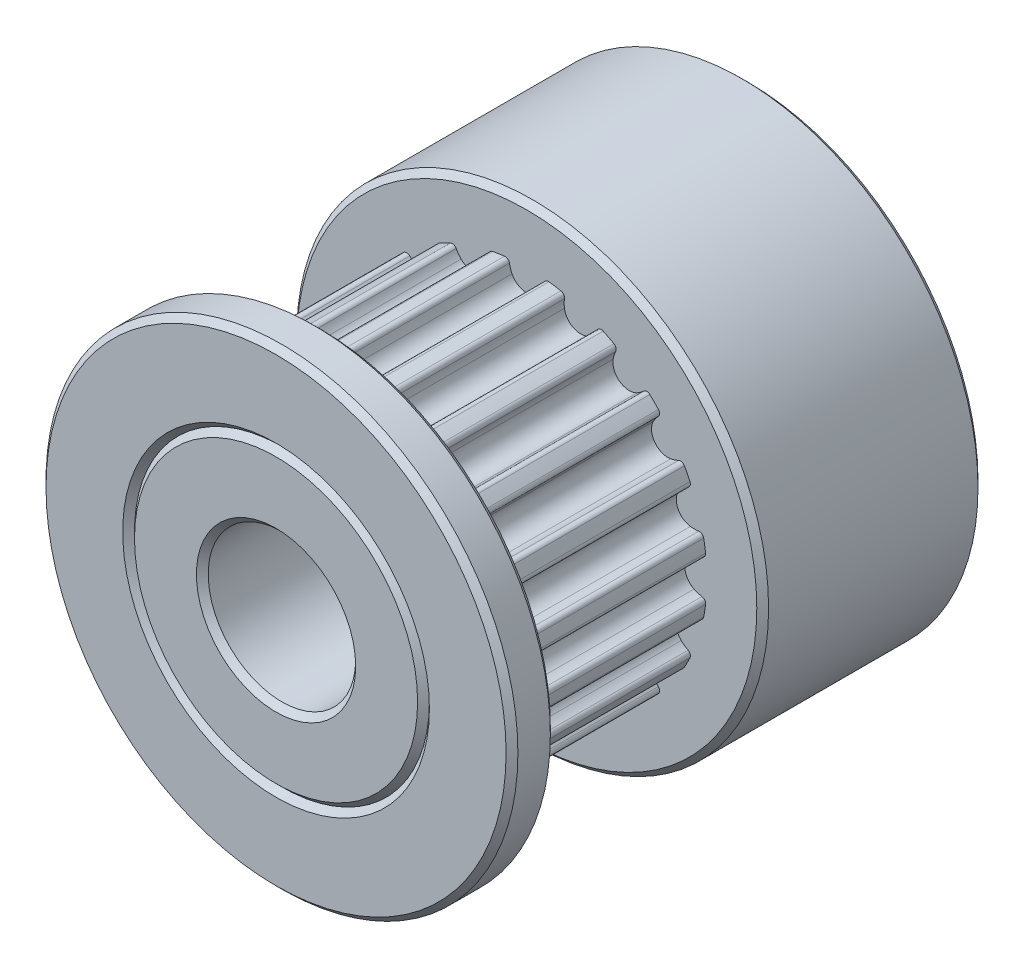
SolidWorks part; units mm, degrees
material "2219-O"
ref_plane "Спереди" through (0, 0, 0) normal (0, 0, 1) x (1, 0, 0)
ref_plane "Сверху" through (0, 0, 0) normal (0, 1, 0) x (1, 0, 0)
ref_plane "Справа" through (0, 0, 0) normal (1, 0, 0) x (0, 0, -1)
sketch "Эскиз2" plane through (0, 0, 0) normal (1, 0, 0) x (0, 0, -1)
  line L0 (-14.5523, 0) -> (18.1217, 0) construction
  line L1 (0, 0) -> (0, 4.8)
  line L2 (0, 8) -> (1.5, 8)
  line L3 (1.5, 8) -> (1.5, 6.11)
  line L4 (1.5, 6.11) -> (8.5, 6.11)
  line L5 (8.5, 6.11) -> (8.5, 8)
  line L6 (8.5, 8) -> (16, 8)
  line L7 (16, 5.2) -> (15.8, 5)
  line L8 (15.8, 5) -> (16, 4.8)
  line L9 (16, 4.8) -> (16, 0)
  line L12 (16, 8) -> (16, 5.2)
  line L13 (0, 5.2) -> (0.2, 5)
  line L14 (0.2, 5) -> (0, 4.8)
  line L15 (0, 5.2) -> (0, 8)
  line L17 (0, 2.5) -> (16, 2.5)
  dimension "D1" = 16
  dimension "D2" = 10
  dimension "D3" = 1.5
  dimension "D4" = 0.2
  dimension "D5" = 16
  dimension "D6" = 5
  dimension "D7" = 7
  dimension "D8" = 12.22
revolve "Повернуть1" add sketch "Эскиз2" angle 360 about L0
chamfer "Фаска1" distance 0.2 angle 45 6 edges at (2.5, 0, 0) (8, 0, -16) (2.5, 0, -16) (8, 0, 0) (8, 0, -1.5) (8, 0, -8.5)
sketch "Эскиз3" plane through (0, 0, 0) normal (0, 0, 1) x (1, 0, 0)
  line L0 (-26.2309, 6.11) -> (36.0031, 6.11) construction
  line L1 (0, 9.858) -> (0, -9.1722) construction
  line L2 (-3.2209, 5.36) -> (39.5424, 5.36) construction
  circle A0 centre (0, 0) radius 6.11 construction
  arc A1 (-0.4989, 5.6718) -> (0.4989, 5.6718) centre (0, 5.915) ccw
  arc A2 (-0.4989, 5.6718) -> (-0.5996, 6.0805) centre (0.4, 6.11) cw
  arc A3 (0.4989, 5.6718) -> (0.5996, 6.0805) centre (-0.4, 6.11) ccw
  arc A4 (-0.5996, 6.0805) -> (0.5996, 6.0805) centre (0, 0) cw
  arc A5 (2.2271, 5.24) -> (2.4492, 5.5976) centre (1.5077, 5.9346) ccw
  arc A6 (1.2782, 5.5484) -> (1.3088, 5.9682) centre (2.2685, 5.6873) cw
  arc A7 (1.3088, 5.9682) -> (2.4492, 5.5976) centre (0, 0) cw
  arc A8 (1.2782, 5.5484) -> (2.2271, 5.24) centre (1.8278, 5.6255) ccw
  arc A9 (3.7374, 4.2953) -> (4.0591, 4.5668) centre (3.2678, 5.1782) ccw
  arc A10 (2.9302, 4.8818) -> (3.089, 5.2717) centre (3.915, 4.708) cw
  arc A11 (3.089, 5.2717) -> (4.0591, 4.5668) centre (0, 0) cw
  arc A12 (2.9302, 4.8818) -> (3.7374, 4.2953) centre (3.4767, 4.7853) ccw
  arc A13 (4.8818, 2.9302) -> (5.2717, 3.089) centre (4.708, 3.915) ccw
  arc A14 (4.2953, 3.7374) -> (4.5668, 4.0591) centre (5.1782, 3.2678) cw
  arc A15 (4.5668, 4.0591) -> (5.2717, 3.089) centre (0, 0) cw
  arc A16 (4.2953, 3.7374) -> (4.8818, 2.9302) centre (4.7853, 3.4767) ccw
  arc A17 (5.5484, 1.2782) -> (5.9682, 1.3088) centre (5.6873, 2.2685) ccw
  arc A18 (5.24, 2.2271) -> (5.5976, 2.4492) centre (5.9346, 1.5077) cw
  arc A19 (5.5976, 2.4492) -> (5.9682, 1.3088) centre (0, 0) cw
  arc A20 (5.24, 2.2271) -> (5.5484, 1.2782) centre (5.6255, 1.8278) ccw
  arc A21 (5.6718, -0.4989) -> (6.0805, -0.5996) centre (6.11, 0.4) ccw
  arc A22 (5.6718, 0.4989) -> (6.0805, 0.5996) centre (6.11, -0.4) cw
  arc A23 (6.0805, 0.5996) -> (6.0805, -0.5996) centre (0, 0) cw
  arc A24 (5.6718, 0.4989) -> (5.6718, -0.4989) centre (5.915, 0) ccw
  arc A25 (5.24, -2.2271) -> (5.5976, -2.4492) centre (5.9346, -1.5077) ccw
  arc A26 (5.5484, -1.2782) -> (5.9682, -1.3088) centre (5.6873, -2.2685) cw
  arc A27 (5.9682, -1.3088) -> (5.5976, -2.4492) centre (0, 0) cw
  arc A28 (5.5484, -1.2782) -> (5.24, -2.2271) centre (5.6255, -1.8278) ccw
  arc A29 (4.2953, -3.7374) -> (4.5668, -4.0591) centre (5.1782, -3.2678) ccw
  arc A30 (4.8818, -2.9302) -> (5.2717, -3.089) centre (4.708, -3.915) cw
  arc A31 (5.2717, -3.089) -> (4.5668, -4.0591) centre (0, 0) cw
  arc A32 (4.8818, -2.9302) -> (4.2953, -3.7374) centre (4.7853, -3.4767) ccw
  arc A33 (2.9302, -4.8818) -> (3.089, -5.2717) centre (3.915, -4.708) ccw
  arc A34 (3.7374, -4.2953) -> (4.0591, -4.5668) centre (3.2678, -5.1782) cw
  arc A35 (4.0591, -4.5668) -> (3.089, -5.2717) centre (0, 0) cw
  arc A36 (3.7374, -4.2953) -> (2.9302, -4.8818) centre (3.4767, -4.7853) ccw
  arc A37 (1.2782, -5.5484) -> (1.3088, -5.9682) centre (2.2685, -5.6873) ccw
  arc A38 (2.2271, -5.24) -> (2.4492, -5.5976) centre (1.5077, -5.9346) cw
  arc A39 (2.4492, -5.5976) -> (1.3088, -5.9682) centre (0, 0) cw
  arc A40 (2.2271, -5.24) -> (1.2782, -5.5484) centre (1.8278, -5.6255) ccw
  arc A41 (-0.4989, -5.6718) -> (-0.5996, -6.0805) centre (0.4, -6.11) ccw
  arc A42 (0.4989, -5.6718) -> (0.5996, -6.0805) centre (-0.4, -6.11) cw
  arc A43 (0.5996, -6.0805) -> (-0.5996, -6.0805) centre (0, 0) cw
  arc A44 (0.4989, -5.6718) -> (-0.4989, -5.6718) centre (0, -5.915) ccw
  arc A45 (-2.2271, -5.24) -> (-2.4492, -5.5976) centre (-1.5077, -5.9346) ccw
  arc A46 (-1.2782, -5.5484) -> (-1.3088, -5.9682) centre (-2.2685, -5.6873) cw
  arc A47 (-1.3088, -5.9682) -> (-2.4492, -5.5976) centre (0, 0) cw
  arc A48 (-1.2782, -5.5484) -> (-2.2271, -5.24) centre (-1.8278, -5.6255) ccw
  arc A49 (-3.7374, -4.2953) -> (-4.0591, -4.5668) centre (-3.2678, -5.1782) ccw
  arc A50 (-2.9302, -4.8818) -> (-3.089, -5.2717) centre (-3.915, -4.708) cw
  arc A51 (-3.089, -5.2717) -> (-4.0591, -4.5668) centre (0, 0) cw
  arc A52 (-2.9302, -4.8818) -> (-3.7374, -4.2953) centre (-3.4767, -4.7853) ccw
  arc A53 (-4.8818, -2.9302) -> (-5.2717, -3.089) centre (-4.708, -3.915) ccw
  arc A54 (-4.2953, -3.7374) -> (-4.5668, -4.0591) centre (-5.1782, -3.2678) cw
  arc A55 (-4.5668, -4.0591) -> (-5.2717, -3.089) centre (0, 0) cw
  arc A56 (-4.2953, -3.7374) -> (-4.8818, -2.9302) centre (-4.7853, -3.4767) ccw
  arc A57 (-5.5484, -1.2782) -> (-5.9682, -1.3088) centre (-5.6873, -2.2685) ccw
  arc A58 (-5.24, -2.2271) -> (-5.5976, -2.4492) centre (-5.9346, -1.5077) cw
  arc A59 (-5.5976, -2.4492) -> (-5.9682, -1.3088) centre (0, 0) cw
  arc A60 (-5.24, -2.2271) -> (-5.5484, -1.2782) centre (-5.6255, -1.8278) ccw
  arc A61 (-5.6718, 0.4989) -> (-6.0805, 0.5996) centre (-6.11, -0.4) ccw
  arc A62 (-5.6718, -0.4989) -> (-6.0805, -0.5996) centre (-6.11, 0.4) cw
  arc A63 (-6.0805, -0.5996) -> (-6.0805, 0.5996) centre (0, 0) cw
  arc A64 (-5.6718, -0.4989) -> (-5.6718, 0.4989) centre (-5.915, 0) ccw
  arc A65 (-5.24, 2.2271) -> (-5.5976, 2.4492) centre (-5.9346, 1.5077) ccw
  arc A66 (-5.5484, 1.2782) -> (-5.9682, 1.3088) centre (-5.6873, 2.2685) cw
  arc A67 (-5.9682, 1.3088) -> (-5.5976, 2.4492) centre (0, 0) cw
  arc A68 (-5.5484, 1.2782) -> (-5.24, 2.2271) centre (-5.6255, 1.8278) ccw
  arc A69 (-4.2953, 3.7374) -> (-4.5668, 4.0591) centre (-5.1782, 3.2678) ccw
  arc A70 (-4.8818, 2.9302) -> (-5.2717, 3.089) centre (-4.708, 3.915) cw
  arc A71 (-5.2717, 3.089) -> (-4.5668, 4.0591) centre (0, 0) cw
  arc A72 (-4.8818, 2.9302) -> (-4.2953, 3.7374) centre (-4.7853, 3.4767) ccw
  arc A73 (-2.9302, 4.8818) -> (-3.089, 5.2717) centre (-3.915, 4.708) ccw
  arc A74 (-3.7374, 4.2953) -> (-4.0591, 4.5668) centre (-3.2678, 5.1782) cw
  arc A75 (-4.0591, 4.5668) -> (-3.089, 5.2717) centre (0, 0) cw
  arc A76 (-3.7374, 4.2953) -> (-2.9302, 4.8818) centre (-3.4767, 4.7853) ccw
  arc A77 (-1.2782, 5.5484) -> (-1.3088, 5.9682) centre (-2.2685, 5.6873) ccw
  arc A78 (-2.2271, 5.24) -> (-2.4492, 5.5976) centre (-1.5077, 5.9346) cw
  arc A79 (-2.4492, 5.5976) -> (-1.3088, 5.9682) centre (0, 0) cw
  arc A80 (-2.2271, 5.24) -> (-1.2782, 5.5484) centre (-1.8278, 5.6255) ccw
  point P152 (0, 0)
  point P492 (0, 0)
  dimension "D1" = 12.22
  dimension "D2" = 0.555
  dimension "D4" = 1
  dimension "D3" = 0.75
extrude "Вырез-Вытянуть4" cut sketch "Эскиз3" against normal up to surface (7 mm away) from offset 1.5 up to face at (7.8, 0, -8.5) offset against normal yes
fillet "Скругление1" radius 0.15 40 edges at (0.5996, 6.0805, -5) (-0.5996, 6.0805, -5) (-1.3088, 5.9682, -5) (-2.4492, 5.5976, -5) (-3.089, 5.2717, -5) (-4.0591, 4.5668, -5) (-4.5668, 4.0591, -5) (-5.2717, 3.089, -5) (-5.5976, 2.4492, -5) (-5.9682, 1.3088, -5) (-6.0805, 0.5996, -5) (-6.0805, -0.5996, -5) (-5.9682, -1.3088, -5) (-5.5976, -2.4492, -5) (-5.2717, -3.089, -5) (-4.5668, -4.0591, -5) (-4.0591, -4.5668, -5) (-3.089, -5.2717, -5) (-2.4492, -5.5976, -5) (-1.3088, -5.9682, -5) (-0.5996, -6.0805, -5) (0.5996, -6.0805, -5) (1.3088, -5.9682, -5) (2.4492, -5.5976, -5) (3.089, -5.2717, -5) (4.0591, -4.5668, -5) (4.5668, -4.0591, -5) (5.2717, -3.089, -5) (5.5976, -2.4492, -5) (5.9682, -1.3088, -5) (6.0805, -0.5996, -5) (6.0805, 0.5996, -5) (5.9682, 1.3088, -5) (5.5976, 2.4492, -5) (5.2717, 3.089, -5) (4.5668, 4.0591, -5) (4.0591, 4.5668, -5) (3.089, 5.2717, -5) (2.4492, 5.5976, -5) (1.3088, 5.9682, -5)
